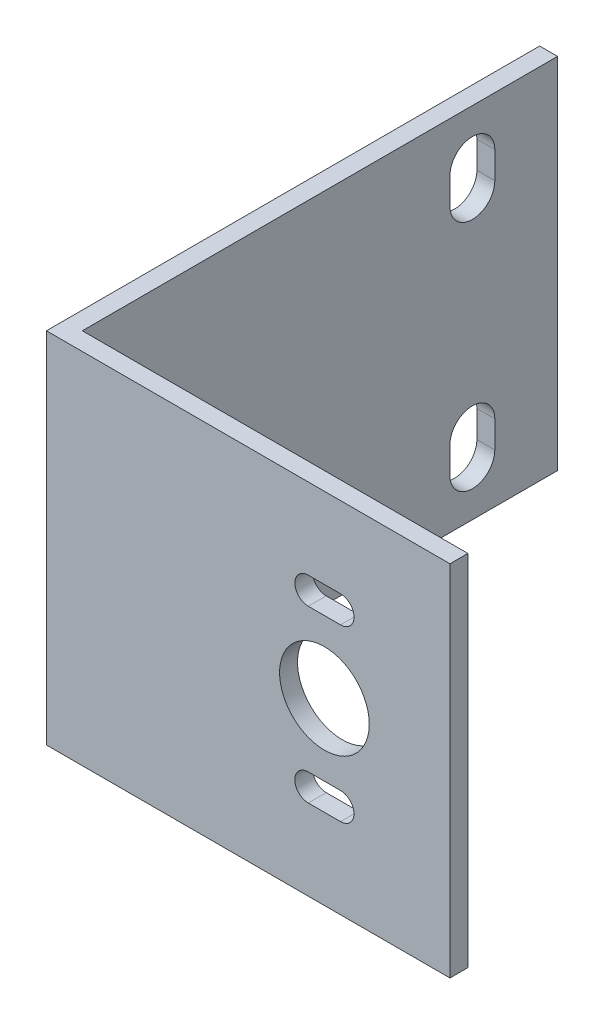
SolidWorks part; units mm, degrees
ref_plane "Plan de face" through (0, 0, 0) normal (0, 0, 1) x (1, 0, 0)
ref_plane "Plan de dessus" through (0, 0, 0) normal (0, 1, 0) x (1, 0, 0)
ref_plane "Plan de droite" through (0, 0, 0) normal (1, 0, 0) x (0, 0, -1)
sketch "Esquisse2" plane through (0, 0, 0) normal (0, 0, 1) x (1, 0, 0)
  line L0 (51.958, 22.6803) -> (6.958, 22.6803)
  line L4 (51.958, 22.6803) -> (51.958, -17.3197)
  line L7 (51.958, -17.3197) -> (6.958, -17.3197)
  line L10 (36.158, 12.1803) -> (39.758, 12.1803) construction
  line L11 (36.158, 13.6803) -> (39.758, 13.6803)
  line L12 (36.158, 10.6803) -> (39.758, 10.6803)
  line L13 (37.958, 2.6803) -> (-38.042, 2.6803) construction
  line L14 (36.158, -6.8197) -> (39.758, -6.8197) construction
  line L15 (36.158, -8.3197) -> (39.758, -8.3197)
  line L16 (36.158, -5.3197) -> (39.758, -5.3197)
  line L17 (6.958, 22.6803) -> (6.958, -17.3197)
  circle A4 centre (37.958, 2.6803) radius 5
  arc A5 (36.158, 13.6803) -> (36.158, 10.6803) centre (36.158, 12.1803) ccw
  arc A6 (39.758, 10.6803) -> (39.758, 13.6803) centre (39.758, 12.1803) ccw
  arc A7 (36.158, -8.3197) -> (36.158, -5.3197) centre (36.158, -6.8197) cw
  arc A8 (39.758, -5.3197) -> (39.758, -8.3197) centre (39.758, -6.8197) cw
  point P20 (37.958, 12.1803)
  point P29 (37.958, -6.8197)
  dimension "D12" = 10
  dimension "D13" = 14
  dimension "D14" = 14
  dimension "D15" = 3
  dimension "D16" = 9.5
  dimension "D17" = 1.8
  dimension "D18" = 45
extrude "Boss.-Extru.8" add sketch "Esquisse2" along normal blind 2
sketch "Esquisse3" plane through (0, 22.6803, 0) normal (0, 1, 0) x (1, 0, 0)
  line L1 (6.958, 0) -> (8.958, 0)
  line L2 (6.958, 0) -> (6.958, 53)
  line L3 (6.958, 53) -> (8.958, 53)
  line L4 (8.958, 0) -> (8.958, 53)
  dimension "D1" = 2
  dimension "D2" = 53
extrude "Boss.-Extru.9" add sketch "Esquisse3" against normal blind 40
sketch "Esquisse4" plane through (8.958, 0, 0) normal (1, 0, 0) x (0, 0, -1)
  line L0 (43.5, -11.8197) -> (43.5, -8.8197) construction
  line L1 (41, -11.8197) -> (41, -8.8197)
  line L2 (46, -11.8197) -> (46, -8.8197)
  line L3 (53, -17.3197) -> (53, 22.6803) construction
  line L4 (0, -17.3197) -> (53, -17.3197) construction
  line L5 (53, 2.6803) -> (0, 2.6803) construction
  line L6 (0, -17.3197) -> (0, 22.6803) construction
  line L7 (43.5, 17.1803) -> (43.5, 14.1803) construction
  line L8 (41, 17.1803) -> (41, 14.1803)
  line L9 (46, 17.1803) -> (46, 14.1803)
  arc A0 (41, -11.8197) -> (46, -11.8197) centre (43.5, -11.8197) ccw
  arc A1 (46, -8.8197) -> (41, -8.8197) centre (43.5, -8.8197) ccw
  arc A2 (41, 17.1803) -> (46, 17.1803) centre (43.5, 17.1803) cw
  arc A3 (46, 14.1803) -> (41, 14.1803) centre (43.5, 14.1803) cw
  point P2 (43.5, -10.3197)
  point P17 (43.5, 15.6803)
  dimension "D1" = 9.5
  dimension "D2" = 7
  dimension "D3" = 5
  dimension "D4" = 1.5
extrude "Enlèv. mat.-Extru.1" cut sketch "Esquisse4" against normal blind 40
